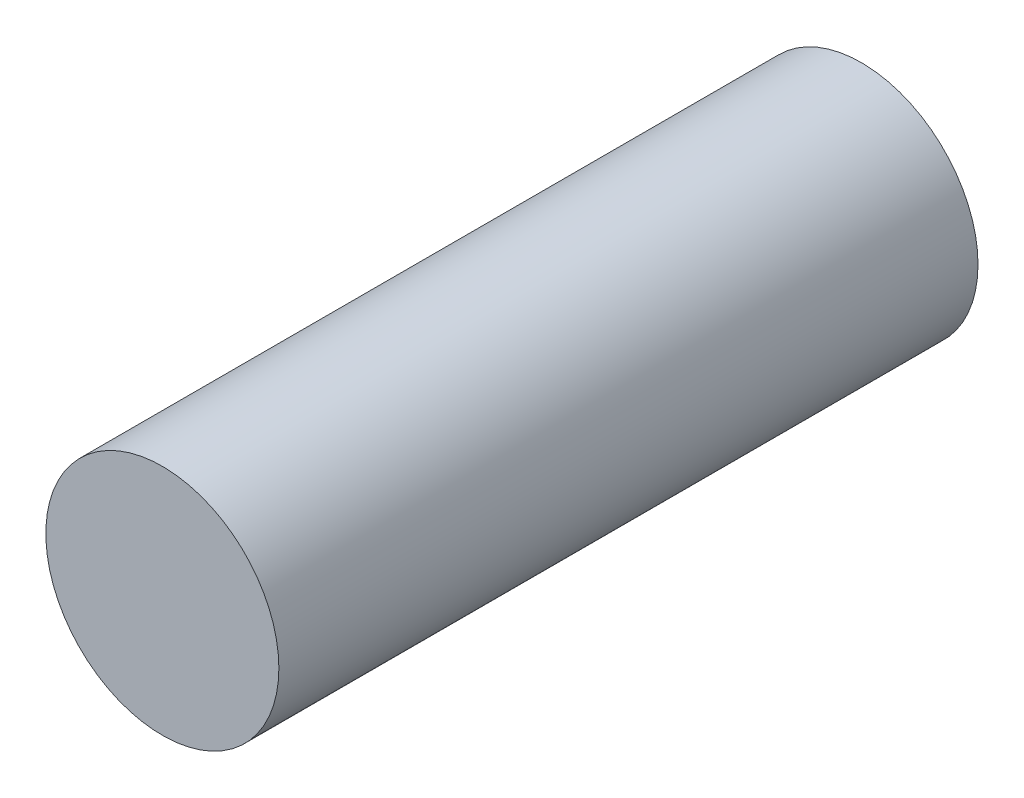
SolidWorks part; units mm, degrees
ref_plane "Front Plane" through (0, 0, 0) normal (0, 0, 1) x (1, 0, 0)
ref_plane "Top Plane" through (0, 0, 0) normal (0, 1, 0) x (1, 0, 0)
ref_plane "Right Plane" through (0, 0, 0) normal (1, 0, 0) x (0, 0, -1)
sketch "Sketch1" plane through (0, 0, 0) normal (0, 0, 1) x (1, 0, 0)
  circle A0 centre (0, 0) radius 12.5
  dimension "D1" = 25
extrude "Boss-Extrude1" add sketch "Sketch1" along normal blind 75
